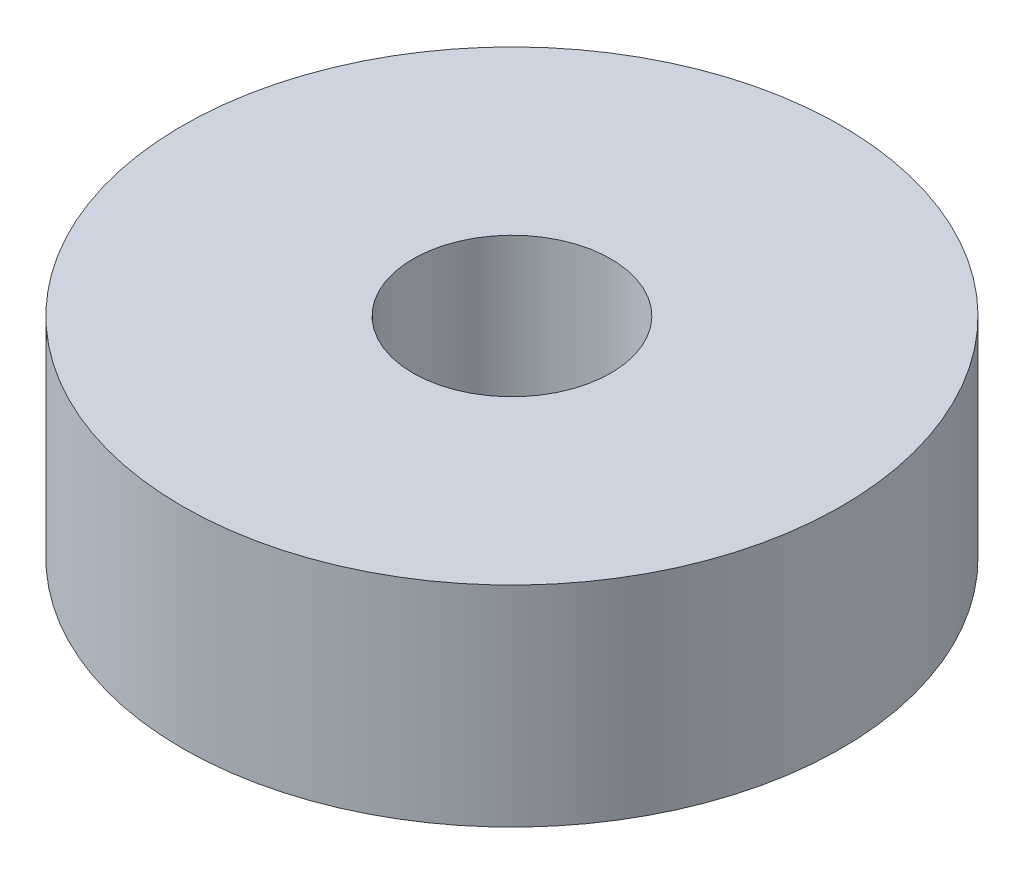
SolidWorks part; units mm, degrees
ref_plane "Front Plane" through (0, 0, 0) normal (0, 0, 1) x (1, 0, 0)
ref_plane "Top Plane" through (0, 0, 0) normal (0, 1, 0) x (1, 0, 0)
ref_plane "Right Plane" through (0, 0, 0) normal (1, 0, 0) x (0, 0, -1)
sketch "Sketch1" plane through (0, 0, 0) normal (0, 1, 0) x (1, 0, 0)
  line L0 (-3.3074, 0.9678) -> (6.6748, 0.9678) construction
  circle A0 centre (1.6837, 0.9678) radius 4.9911
  circle A1 centre (1.6837, 0.9678) radius 1.4986
  point P43 (0, 0)
  point P44 (0, 0)
  dimension "D1" = 2.9972
  dimension "D3" = 9.9822
extrude "Boss-Extrude1" add sketch "Sketch1" along normal blind 3.175
